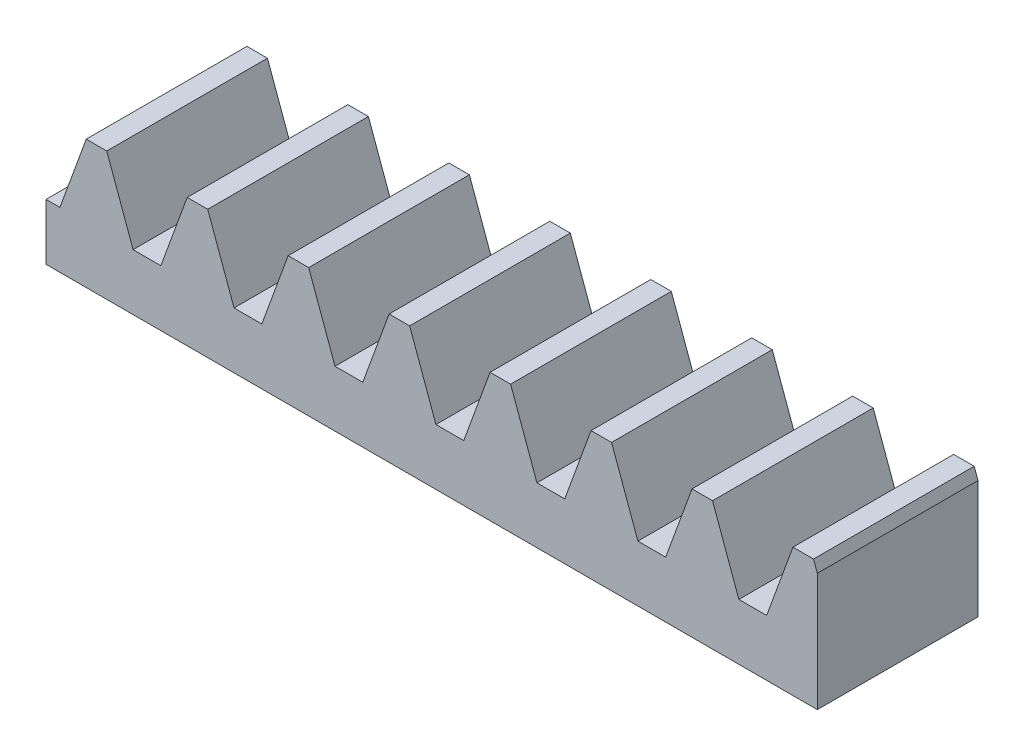
SolidWorks part; units mm, degrees
extrude "Blank" add sketch "BlankSke" against normal blind 63.5
sketch "BlankSke" plane through (0, 0, 0) normal (0, 0, 1) x (1, 0, 0)
  line L1 (0, 0) -> (304.8, 0)
  line L2 (0, 0) -> (0, 50.8)
  line L3 (0, 50.8) -> (304.8, 50.8)
  line L4 (304.8, 0) -> (304.8, 50.8)
  dimension "Length" = 304.8
ref_plane "Plane1" through (0, 0, 0) normal (0, 0, 1) x (1, 0, 0)
ref_plane "Plane2" through (0, 0, 0) normal (0, 1, 0) x (1, 0, 0)
ref_plane "Plane3" through (0, 0, 0) normal (1, 0, 0) x (0, 0, -1)
sketch "HoldingSke" plane through (0, 0, 0) normal (0, 1, 0) x (1, 0, 0)
  line L0 (0, 0) -> (38.9151, -32.6536)
  line L1 (-15, 0) -> (100, 0) construction
  line L2 (0, 0) -> (-2.1039, 2.3779)
  line L3 (0, 0) -> (-11.863, 4.5341)
  line L4 (0, 0) -> (8.5297, 1.351)
  line L5 (0, 0) -> (-23.7986, -8.8762)
  line L6 (0, 0) -> (-10.5278, -7.1032)
  line L9 (-71.009, 38.7566) -> (215.4093, 143.0043)
  line L10 (-76.2, 71.12) -> (-38.1, 71.12)
  line L11 (0, 0) -> (-63.5, 0)
  line L12 (-76.2, 101.6) -> (-75.7682, 101.6)
  line L13 (24.9733, 27.94) -> (52.9518, 28.4284)
  line L14 (24.9733, 27.94) -> (24.9746, 27.94)
  line L15 (24.9733, 27.94) -> (100.4006, 29.5858)
  circle A0 centre (0, 0) radius 19.05
  circle A1 centre (0, 0) radius 19.05
  circle A2 centre (0, 0) radius 12.7
  dimension "MPH" = 38.1
  dimension "Diameter" = 38.1
  dimension "Show_teeth" = 400
  dimension "Thickness" = 12.7
  dimension "Ap" = 20
  dimension "Pitch_height" = 38.1
  dimension "Width" = 63.5
  dimension "Addendum_fac" = 1
  dimension "Dedendum_fac" = 1.25
  dimension "Clearance_fac" = 0.25
  dimension "Dedendum_add" = 0.0013
  dimension "Length" = 304.8
sketch "TooCutSkeIll" plane through (0, 0, 0) normal (0, 0, 1) x (1, 0, 0)
  line L0 (-15.7707, 50.4657) -> (-6.2526, 24.3149)
  line L1 (-3.2679, 22.225) -> (3.2679, 22.225)
  line L2 (6.2526, 24.3149) -> (15.7707, 50.4657)
  line L3 (304.8, 50.8) -> (0, 50.8) construction
  line L4 (0, 0) -> (0, 64.897) construction
  line L5 (-13.208, 38.1) -> (12.954, 38.1) construction
  line L6 (0, 0) -> (304.8, 0) construction
  line L7 (11.27, 38.1) -> (11.27, 48.7463) construction
  line L8 (-11.27, 38.1) -> (-11.27, 48.7463) construction
  line L9 (16.2481, 50.8) -> (16.2481, 50.8254)
  line L10 (-16.2481, 50.8) -> (-16.2481, 50.8254)
  line L11 (-16.2481, 50.8254) -> (16.2481, 50.8254)
  arc A0 (3.2679, 22.225) -> (6.2526, 24.3149) centre (3.2679, 25.4013) ccw
  arc A1 (-6.2526, 24.3149) -> (-3.2679, 22.225) centre (-3.2679, 25.4013) ccw
  arc A2 (16.2481, 50.8) -> (15.7707, 50.4657) centre (16.2481, 50.292) ccw
  arc A3 (-15.7707, 50.4657) -> (-16.2481, 50.8) centre (-16.2481, 50.292) ccw
  dimension "Pitch_height" = 38.1
  dimension "Pressure_angle" = 20
extrude "ToothCutIll" [suppressed] cut sketch "TooCutSkeIll" against normal through all
sketch "TooCutSkeSim" plane through (0, 0, 0) normal (0, 0, 1) x (1, 0, 0)
  line L0 (5.4919, 22.225) -> (-5.4919, 22.225)
  line L1 (15.9016, 50.8254) -> (5.4919, 22.225)
  line L2 (0, 17.4625) -> (0, 53.467) construction
  line L3 (15.9016, 50.8254) -> (-15.9016, 50.8254)
  line L6 (-15.9016, 50.8254) -> (-5.4919, 22.225)
  line L9 (-11.27, 38.1) -> (11.27, 38.1) construction
  line L10 (0, 0) -> (304.8, 0) construction
  line L11 (11.27, 38.1) -> (11.27, 53.467) construction
  line L12 (-11.27, 38.1) -> (-11.27, 53.467) construction
  dimension "Pitch_height" = 38.1
  dimension "Pressure_angle" = 20
extrude "ToothCutSim" cut sketch "TooCutSkeSim" against normal through all
pattern_linear "TeethCuts" count 8 spacing 39.8982 along (1, 0, 0) of "ToothCutIll", "ToothCutSim"
equation "' \"Pitch@HoldingSke\" = 4"
equation "' \"Num_teeth@HoldingSke\" = 12"
equation "' \"Ap@HoldingSke\" =  20"
equation "' \"Ap@HoldingSke\" = 20"
equation "' \"Width@HoldingSke\" = 0.25"
equation "' \"Show_teeth@HoldingSke\" = 500"
equation "' \"Backlash@HoldingSke\" = 0.009"
equation "' \"Addendum_fac@HoldingSke\" = 1.0"
equation "' \"Dedendum_fac@HoldingSke\" = 1.25"
equation "' \"Dedendum_add@HoldingSke\" = 0.00005"
equation "' \"Clearance_fac@HoldingSke\" = 0.25"
equation "' \"Pitch_height@HoldingSke\" = 1"
equation "' \"Length@HoldingSke\" = 4.71"
equation "\"MPH@HoldingSke\" = \"Dedendum_fac@HoldingSke\" / \"Pitch@HoldingSke\" + 2 * \"Dedendum_add@HoldingSke\" + 0.002"
equation "\"MPH@HoldingSke\" = ((sgn( \"MPH@HoldingSke\" - \"Pitch_height@HoldingSke\")+1)*( \"MPH@HoldingSke\" - \"Pitch_height@HoldingSke\"))/2 + \"Pitch_height@HoldingSke\""
equation "\"Blank_height@BlankSke\" = \"Pitch_height@HoldingSke\" + \"Addendum_fac@HoldingSke\"  / \"Pitch@HoldingSke\" "
equation "\"Length@BlankSke\" =  \"Length@HoldingSke\""
equation "\"Face_width@Blank\" = \"Width@HoldingSke\""
equation "\"Pressure_angle@TooCutSkeIll\" = \"Ap@HoldingSke\""
equation "\"Addendum_plus@TooCutSkeIll\" =  \"Addendum_fac@HoldingSke\"  / \"Pitch@HoldingSke\" + 0.001"
equation "\"Dedendum@TooCutSkeIll\" = \"Dedendum_fac@HoldingSke\"  / \"Pitch@HoldingSke\""
equation "\"Pitch_height@TooCutSkeIll\" =  \"MPH@HoldingSke\""
equation "\"Gap_width@TooCutSkeIll\" = 3.14159265 / 2 / \"Pitch@HoldingSke\" + 6 * \"Backlash@HoldingSke\""
equation "\"Pressure_angle@TooCutSkeSim\" = \"Ap@HoldingSke\""
equation "\"Addendum_plus@TooCutSkeSim\" =  \"Addendum_fac@HoldingSke\"  / \"Pitch@HoldingSke\" + 0.001"
equation "\"Dedendum@TooCutSkeSim\" = \"Dedendum_fac@HoldingSke\"  / \"Pitch@HoldingSke\""
equation "\"Pitch_height@TooCutSkeSim\" =  \"MPH@HoldingSke\""
equation "\"Gap_width@TooCutSkeSim\" = 3.14159265 / 2 / \"Pitch@HoldingSke\" + 6 * \"Backlash@HoldingSke\""
equation "\"Root_fillet@TooCutSkeIll\" = \"Clearance_fac@HoldingSke\" / \"Pitch@HoldingSke\" + \"Dedendum_add@HoldingSke\""
equation "\"Break_rad@TooCutSkeIll\" = 0.02 / \"Pitch@HoldingSke\" * 2"
equation "\"Linear_pitch@TeethCuts\" = 3.14159265 / \"Pitch@HoldingSke\""
equation "\"Num_teeth@HoldingSke\" = int( ( \"Length@HoldingSke\" + 0 ) / (3.14159265 / \"Pitch@HoldingSke\")) + 0.9999  + 1"
equation " \"Num_teeth@TeethCuts\" = int( \"Show_teeth@HoldingSke\" ) + 1"
equation " \"Num_teeth@TeethCuts\" = ((sgn( \"Num_teeth@TeethCuts\" - \"Num_teeth@HoldingSke\" )-1)*( \"Num_teeth@TeethCuts\" - \"Num_teeth@HoldingSke\" ))/-2+ \"Num_teeth@HoldingSke\""
equation " \"Num_teeth@TeethCuts\" = ((sgn( \"Num_teeth@TeethCuts\" - 2.0)+1)*( \"Num_teeth@TeethCuts\" - 2.0))/2 +2.0"
